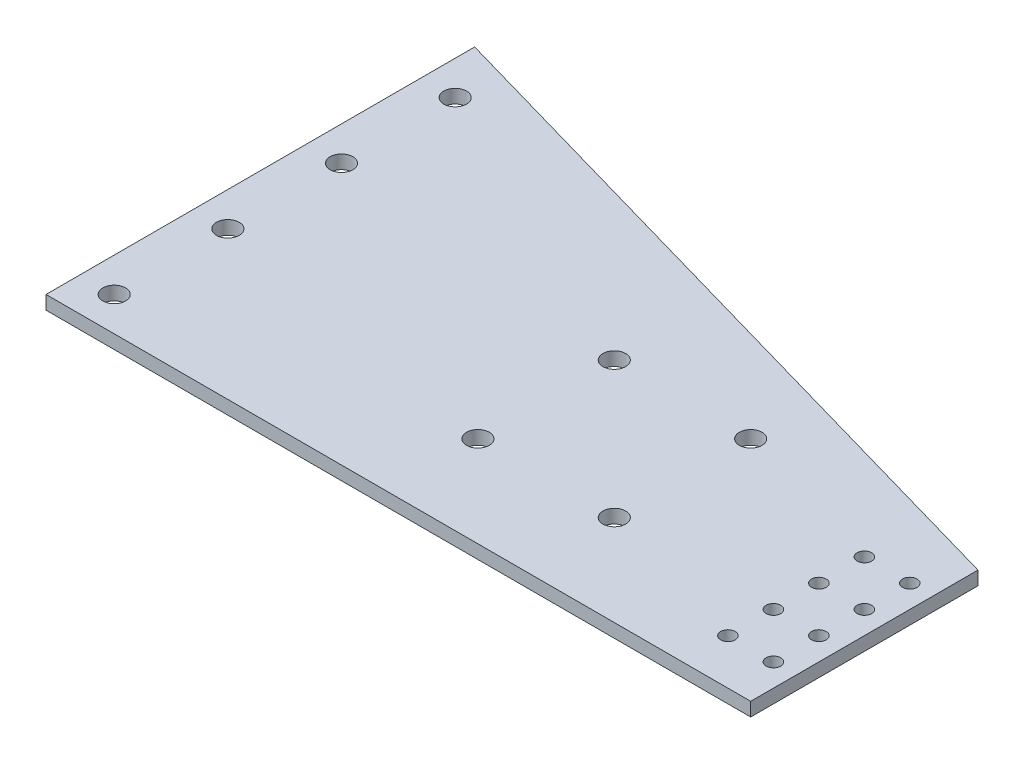
SolidWorks part; units mm, degrees
ref_plane "前视基准面" through (0, 0, 0) normal (0, 0, 1) x (1, 0, 0)
ref_plane "上视基准面" through (0, 0, 0) normal (0, 1, 0) x (1, 0, 0)
ref_plane "右视基准面" through (0, 0, 0) normal (1, 0, 0) x (0, 0, -1)
sketch "草图1" plane through (0, 0, 0) normal (0, 1, 0) x (1, 0, 0)
  line L0 (70, -45) -> (70, 5)
  line L1 (-85, 45) -> (70, 45)
  line L2 (-85, 45) -> (-85, -45)
  line L3 (-85, -45) -> (70, -45)
  line L4 (70, 45) -> (70, -45)
  line L5 (-85, 45) -> (70, -45) construction
  line L6 (-85, -45) -> (70, 45) construction
  line L7 (-70, 45) -> (70, 5)
  line L8 (-85, 45) -> (-70, 45)
  line L9 (-70, 45) -> (-85, 49.2857)
  line L10 (-85, 49.2857) -> (-85, 45)
  point P0 (0, 0)
extrude "凸台-拉伸1" add sketch "草图1" along normal blind 3 contours L7 L1 L2 L3 L0 | L9 L10 L1
hole_wizard "Ø5.0 (5) 直径孔2" positions "草图3" profile "草图2" hole size "Ø5.0" standard "GB" end condition through all
sketch "草图3" plane through (0, 3, 0) normal (0, 1, 0) x (1, 0, 0)
  line L0 (-85, -37.5) -> (-77.5, -37.5)
  line L1 (-85, 49.2857) -> (-85, -45) construction
  line L2 (-77.5, -37.5) -> (-77.5, -45)
  line L3 (-85, -45) -> (70, -45) construction
  line L4 (-77.5, -37.5) -> (-77.5, -12.5)
  line L5 (-77.5, 45) -> (-77.5, 37.5)
  line L6 (-85, 45) -> (-70, 45) construction
  line L7 (-77.5, 37.5) -> (-85, 37.5)
  line L9 (-77.5, 37.5) -> (-77.5, 12.5)
  point P2 (-77.5, -37.5)
  point P14 (-77.5, -12.5)
  point P20 (-77.5, 37.5)
  point P27 (-77.5, 12.5)
sketch "草图2" plane through (-77.5, 3, 37.5) normal (1, 0, 0) x (0, 0, 1)
  line L0 (0, 0) -> (0, 3)
  line L1 (0, 3) -> (2.5, 3)
  line L2 (2.5, 3) -> (2.5, 0)
  line L5 (2.5, 0) -> (0, 0)
  line L11 (0, -6.35) -> (0, 107.95) construction
  dimension "通孔孔直径" = 5
  dimension "通孔孔深度" = 3
hole_wizard "Ø5.0 (5) 直径孔1" positions "草图5" profile "草图4" hole size "Ø5.0" standard "GB" end condition up to next
sketch "草图5" plane through (0, 0, 0) normal (0, -1, 0) x (-1, 0, 0)
  line L0 (85, -25) -> (10, -25)
  line L1 (85, 49.2857) -> (85, -45) construction
  line L5 (10, -25) -> (10, 5)
  line L6 (10, 5) -> (-20, 5)
  line L7 (85, -45) -> (85, -25)
  point P2 (10, -25)
  point P14 (10, 5)
  point P15 (-20, 5)
  point P23 (-20, -25)
sketch "草图4" plane through (-10, 0, 25) normal (1, 0, 0) x (0, 0, -1)
  line L0 (0, 0) -> (0, 3)
  line L1 (0, 3) -> (2.5, 3)
  line L2 (2.5, 3) -> (2.5, 0)
  line L5 (2.5, 0) -> (0, 0)
  line L11 (0, -6.35) -> (0, 107.95) construction
  dimension "通孔孔直径" = 5
  dimension "通孔孔深度" = 3
hole_wizard "Ø3.2 (3.2) 直径孔2" positions "草图7" profile "草图6" hole size "Ø3.2" standard "GB" end condition through all
sketch "草图7" plane through (0, 0, 0) normal (0, -1, 0) x (-1, 0, 0)
  line L0 (-70, -35) -> (-65, -35)
  line L1 (-70, -45) -> (-70, 5) construction
  line L2 (-65, -35) -> (-65, -45)
  line L3 (85, -45) -> (-70, -45) construction
  point P2 (-65, -35)
sketch "草图6" plane through (65, 0, 35) normal (1, 0, 0) x (0, 0, -1)
  line L0 (0, 0) -> (0, 3)
  line L1 (0, 3) -> (1.6, 3)
  line L2 (1.6, 3) -> (1.6, 0)
  line L5 (1.6, 0) -> (0, 0)
  line L11 (0, -6.35) -> (0, 107.95) construction
  dimension "通孔孔直径" = 3.2
  dimension "通孔孔深度" = 3
pattern_linear "阵列(线性)1" count 4 spacing 10 along (0, 0, -1) count 2 spacing 10 along (-1, 0, 0) of "Ø3.2 (3.2) 直径孔2"
